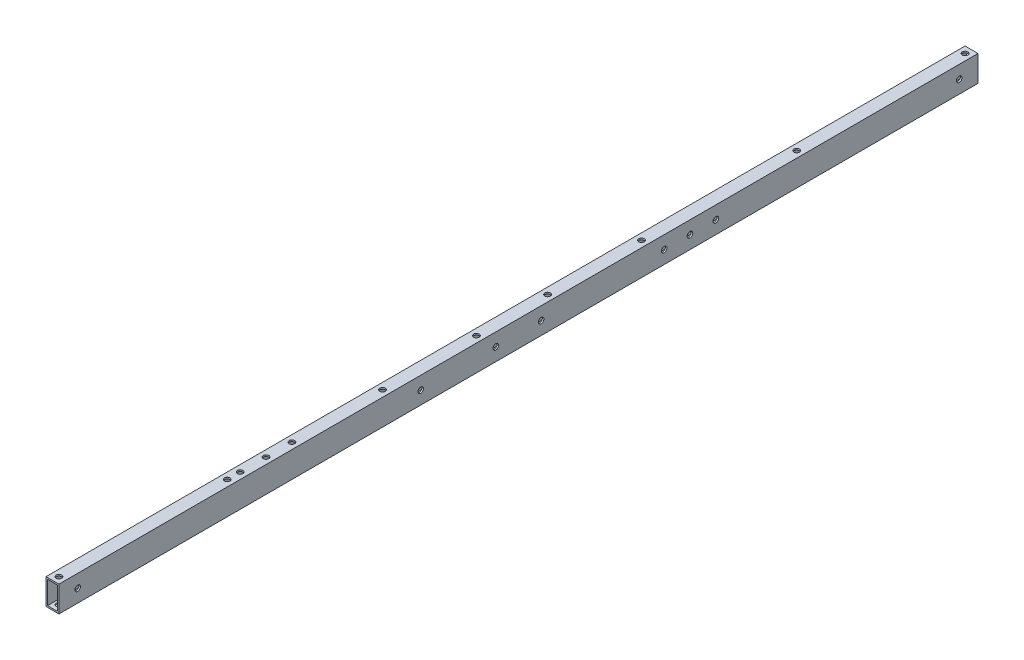
SolidWorks part; units mm, degrees
material "5052-H34"
ref_plane "正面" through (0, 0, 0) normal (0, 0, 1) x (1, 0, 0)
ref_plane "平面" through (0, 0, 0) normal (0, 1, 0) x (1, 0, 0)
ref_plane "右側面" through (0, 0, 0) normal (1, 0, 0) x (0, 0, -1)
sketch "ｽｹｯﾁ1" plane through (0, 0, 0) normal (0, 0, 1) x (1, 0, 0)
  line L1 (-5, 10) -> (5, 10)
  line L2 (-5, 10) -> (-5, -10)
  line L3 (-5, -10) -> (5, -10)
  line L4 (5, 10) -> (5, -10)
  line L5 (-5, 10) -> (5, -10) construction
  line L6 (-5, -10) -> (5, 10) construction
  point P0 (0, 0)
  dimension "D1" = 10
  dimension "D2" = 20
extrude "押し出し-薄板1" add sketch "ｽｹｯﾁ1" along normal blind 710 thin
sketch "ｽｹｯﾁ2" plane through (0, 10, 0) normal (0, 1, 0) x (1, 0, 0)
  line L0 (-5, -355) -> (5, -355) construction
  line L1 (-5, -710) -> (-5, 0) construction
  line L2 (5, -710) -> (5, 0) construction
  line L3 (0, 0) -> (0, -135) construction
  line L4 (0, -355) -> (0, -255) construction
  line L5 (0, -525) -> (0, -565) construction
  circle A0 centre (0, -135) radius 2.15
  circle A1 centre (0, -5) radius 2.15
  circle A2 centre (0, -575) radius 2.15
  circle A3 centre (0, -705) radius 2.15
  circle A4 centre (0, -255) radius 2.15
  circle A5 centre (0, -455) radius 2.15
  circle A6 centre (0, -565) radius 2.15
  circle A7 centre (0, -525) radius 2.15
  circle A8 centre (0, -545) radius 2.15
  circle A9 centre (0, -327.5) radius 2.15
  circle A10 centre (0, -382.5) radius 2.15
  dimension "D1" = 4.3
  dimension "D4" = 4.3
  dimension "D6" = 4.3
  dimension "D11" = 4.3
  dimension "D7" = 190
  dimension "D2" = 5
  dimension "D3" = 130
  dimension "D5" = 200
  dimension "D8" = 40
  dimension "D9" = 55
extrude "ｶｯﾄ - 押し出し1" cut sketch "ｽｹｯﾁ2" against normal through all
sketch "ｽｹｯﾁ3" plane through (5, 0, 0) normal (1, 0, 0) x (0, 0, -1)
  line L0 (-222.5, 10) -> (-222.5, -10) construction
  line L2 (-222.5, 0) -> (-430.5, 0) construction
  line L3 (-222.5, 0) -> (-202.5, 0) construction
  line L4 (-355, -10) -> (-355, 10) construction
  line L5 (-710, -10) -> (0, -10) construction
  line L6 (-710, 10) -> (0, 10) construction
  circle A2 centre (-202.5, 0) radius 2.15
  circle A3 centre (-222.5, 0) radius 2.15
  circle A4 centre (-242.5, 0) radius 2.15
  circle A7 centre (-430.5, 0) radius 2.15
  circle A8 centre (-14.5, 0) radius 2.15
  circle A9 centre (-695.5, 0) radius 2.15
  circle A10 centre (-372.5, 0) radius 2.15
  circle A11 centre (-337.5, 0) radius 2.15
  dimension "D1" = 132.5
  dimension "D4" = 4.3
  dimension "D9" = 4.3
  dimension "D6" = 4.3
  dimension "D2" = 35
  dimension "D5" = 40
  dimension "D7" = 10
  dimension "D8" = 208
extrude "ｶｯﾄ - 押し出し2" cut sketch "ｽｹｯﾁ3" against normal through all
sketch "ｽｹｯﾁ4" plane through (5, 0, 0) normal (1, 0, 0) x (0, 0, -1)
  line L0 (-710, 0) -> (0, 0) construction
  line L1 (-710, -10) -> (-710, 10) construction
  line L2 (-355, 10) -> (-355, -10) construction
  line L3 (-710, 10) -> (0, 10) construction
  line L4 (-710, -10) -> (0, -10) construction
  line L5 (-683, 0) -> (-653, 0) construction
  line L6 (-416.5, 0) -> (-386.5, 0) construction
  line L7 (-293.5, 0) -> (-263.5, 0) construction
  circle A0 centre (-683, 0) radius 6
  circle A1 centre (-653, 0) radius 6
  circle A2 centre (-623, 0) radius 6
  circle A3 centre (-593, 0) radius 6
  circle A4 centre (-563, 0) radius 6
  circle A5 centre (-533, 0) radius 6
  circle A6 centre (-503, 0) radius 6
  circle A7 centre (-473, 0) radius 6
  circle A18 centre (-177, 0) radius 6
  circle A19 centre (-147, 0) radius 6
  circle A20 centre (-117, 0) radius 6
  circle A21 centre (-87, 0) radius 6
  circle A22 centre (-57, 0) radius 6
  circle A23 centre (-27, 0) radius 6
  circle A24 centre (-416.5, 0) radius 6
  circle A26 centre (-386.5, 0) radius 6
  circle A27 centre (-323.5, 0) radius 6
  circle A28 centre (-293.5, 0) radius 6
  circle A29 centre (-355, 0) radius 6
  circle A30 centre (-443, 0) radius 6
  circle A31 centre (-263.5, 0) radius 6
  point P11 (-695.5, 0)
  point P12 (-430.5, 0)
  point P14 (-372.5, 0)
  dimension "D1" = 12
  dimension "D2" = 265
  dimension "D3" = 12.5
  dimension "D5" = 30
  dimension "D6" = 12.5
  dimension "D7" = 58
  dimension "D8" = 14
  dimension "D10" = 30
  dimension "D11" = 14
  dimension "D13" = 30
  dimension "D4" = 9
  dimension "D9" = 2
  dimension "D12" = 2
extrude "-16g" [suppressed] cut sketch "ｽｹｯﾁ4" against normal through all
